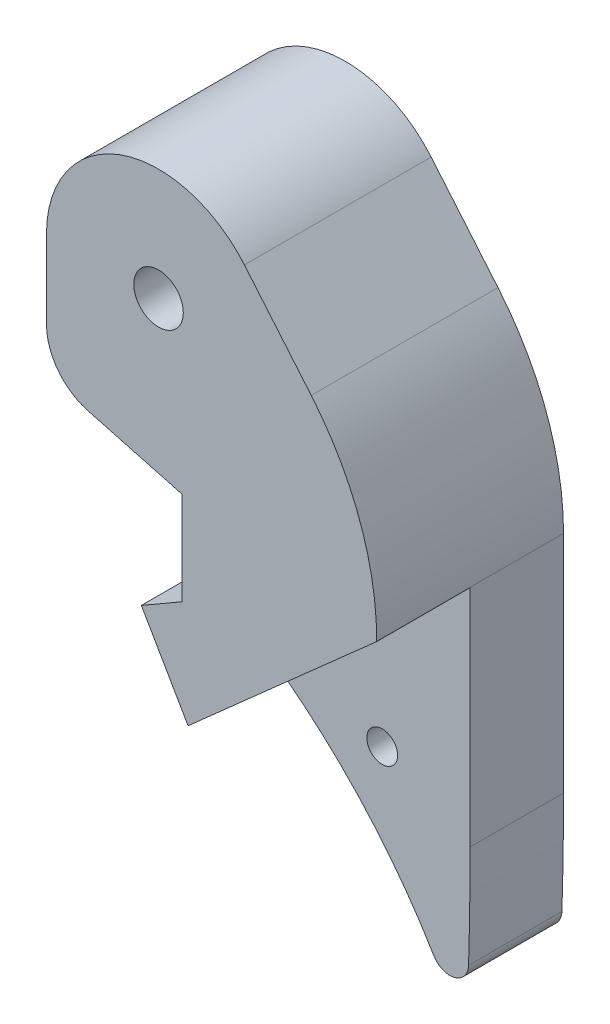
SolidWorks part; units mm, degrees
material "POM 乙缩醛共聚物"
ref_plane "前视基准面" through (0, 0, 0) normal (0, 0, 1) x (1, 0, 0)
ref_plane "上视基准面" through (0, 0, 0) normal (0, 1, 0) x (1, 0, 0)
ref_plane "右视基准面" through (0, 0, 0) normal (1, 0, 0) x (0, 0, -1)
sketch "草图1" plane through (0, 0, 0) normal (0, 0, 1) x (1, 0, 0)
  line L0 (0, 0) -> (0, 13)
  line L2 (0, 0) -> (14.4889, -3.8823)
  line L3 (14.4889, -3.8823) -> (14.4889, -13.8823)
  line L7 (10.1588, -16.3823) -> (14.4889, -13.8823)
  line L13 (10.1588, -16.3823) -> (15.1588, -25.0425)
  line L15 (35.3657, 3.8226) -> (21.1925, 20.7135)
  line L16 (35.3657, -31.1774) -> (35.3657, 3.8226)
  arc A0 (0, 13) -> (21.1925, 20.7135) centre (12, 13) cw
  circle A4 centre (12, 13) radius 2.65
  arc A6 (15.1588, -25.0425) -> (34.8861, -49.7649) centre (-22.7858, -75.5526) cw
  arc A7 (34.8861, -49.7649) -> (35.3657, -31.1774) centre (-325.0868, -31.1774) ccw
  dimension "D3" = 5
  dimension "D6" = 12
  dimension "D4" = 5.3
  dimension "D9" = 10
  dimension "D1" = 15
  dimension "D2" = 120
  dimension "D5" = 105
  dimension "D7" = 10
  dimension "D8" = 13
  dimension "D12" = 35
  dimension "D14" = 35
extrude "凸台-拉伸1" add sketch "草图1" along normal blind 20
sketch "草图2" plane through (0, 0, 20) normal (0, 0, 1) x (1, 0, 0)
  line L0 (15.1588, -25.0425) -> (35.3657, -7.1321)
  line L5 (35.3657, -31.1774) -> (35.3657, 3.8226) construction
  line L6 (35.3657, -7.1321) -> (35.3657, -70.8877)
  line L7 (35.3657, -70.8877) -> (13.7588, -70.8877)
  line L8 (13.7588, -70.8877) -> (15.1588, -25.0425)
extrude "切除-拉伸1" cut sketch "草图2" against normal blind 10
fillet "圆角1" radius 2 1 edges at (34.8861, -49.7649, 5)
fillet "圆角2" radius 30 1 edges at (35.3657, 3.8226, 10)
sketch "草图3" plane through (0, 0, 10) normal (0, 0, 1) x (1, 0, 0)
  circle A0 centre (25.95, -26.5816) radius 1.65
  dimension "D1" = 3.3
extrude "切除-拉伸2" cut sketch "草图3" against normal through all
fillet "圆角3" radius 6 1 edges at (0, 0, 10)
